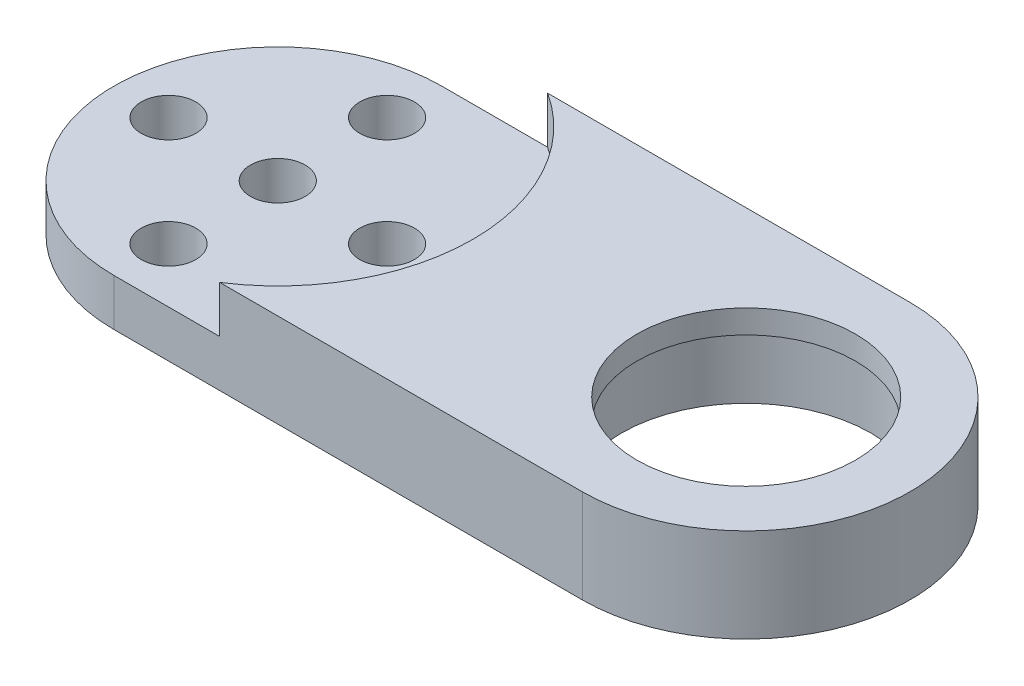
SolidWorks part; units mm, degrees
ref_plane "Front Plane" through (0, 0, 0) normal (0, 0, 1) x (1, 0, 0)
ref_plane "Top Plane" through (0, 0, 0) normal (0, 1, 0) x (1, 0, 0)
ref_plane "Right Plane" through (0, 0, 0) normal (1, 0, 0) x (0, 0, -1)
sketch "Sketch2" plane through (0, 0, 0) normal (0, 1, 0) x (1, 0, 0)
  line L0 (15, 0) -> (-15, 0) construction
  line L1 (15, 10.5) -> (-15, 10.5)
  line L2 (15, -10.5) -> (-15, -10.5)
  arc A0 (15, 10.5) -> (15, -10.5) centre (15, 0) cw
  arc A1 (-15, 10.5) -> (-15, -10.5) centre (-15, 0) ccw
  point P4 (0, 0)
  dimension "D1" = 30
  dimension "D2" = 10.5
  dimension "D3" = 10.5
extrude "Boss-Extrude1" add sketch "Sketch2" along normal blind 6
sketch "Sketch4" plane through (0, 6, 0) normal (0, 1, 0) x (1, 0, 0)
  line L0 (-15, 0) -> (-8, 0) construction
  line L1 (15, 0) -> (-15, 0) construction
  line L2 (-15, 0) -> (-8, 0) construction
  circle A0 centre (-15, 0) radius 1.75
  circle A1 centre (-8, 0) radius 1.75
  circle A2 centre (-15, -7) radius 1.75
  circle A3 centre (-22, 0) radius 1.75
  circle A4 centre (-15, 7) radius 1.75
  dimension "D1" = 3.5
  dimension "D2" = 7
  dimension "D3" = 4
extrude "Servo horn holes" cut sketch "Sketch4" against normal through all
sketch "Sketch5" plane through (0, 0, 0) normal (0, -1, 0) x (-1, 0, 0)
  circle A0 centre (-15, 0) radius 8
  dimension "D1" = 16
extrude "Bearing press fit" cut sketch "Sketch5" against normal blind 4.5
sketch "Sketch6" plane through (0, 6, 0) normal (0, 1, 0) x (1, 0, 0)
  circle A0 centre (15, 0) radius 10.5
  circle A1 centre (15, 0) radius 7
  dimension "D1" = 14
extrude "Boss-Extrude2" [suppressed] add sketch "Sketch6" along normal blind 2
sketch "Sketch7" plane through (0, 6, 0) normal (0, 1, 0) x (1, 0, 0)
  circle A0 centre (-15, 0) radius 12.5
  dimension "D1" = 25
extrude "Cut-Extrude1" cut sketch "Sketch7" against normal blind 3
sketch "Sketch8" plane through (0, 4.5, 0) normal (0, -1, 0) x (1, 0, 0)
  circle A0 centre (15, 0) radius 7
  dimension "D1" = 14
extrude "Cut-Extrude2" cut sketch "Sketch8" against normal through all
